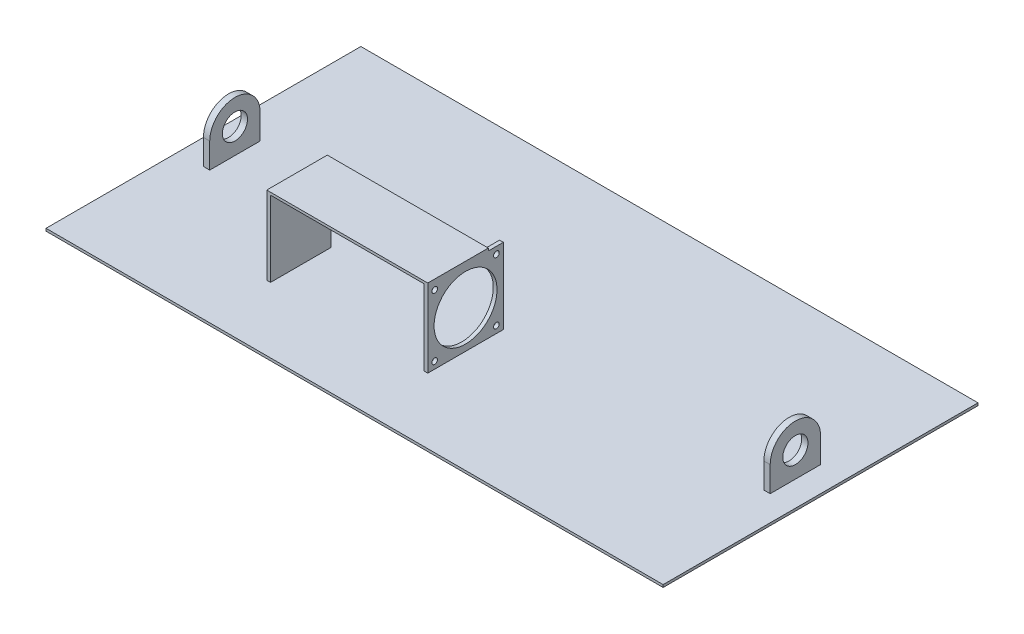
SolidWorks part; units mm, degrees
ref_plane "前视基准面" through (0, 0, 0) normal (0, 0, 1) x (1, 0, 0)
ref_plane "上视基准面" through (0, 0, 0) normal (0, 1, 0) x (1, 0, 0)
ref_plane "右视基准面" through (0, 0, 0) normal (1, 0, 0) x (0, 0, -1)
sketch "草图1" plane through (0, 0, 0) normal (0, 1, 0) x (1, 0, 0)
  line L0 (0, 0) -> (490, 0)
  line L1 (490, 0) -> (490, 250)
  line L2 (490, 250) -> (0, 250)
  line L3 (0, 250) -> (0, 0)
  dimension "D1" = 490
  dimension "D2" = 250
extrude "凸台-拉伸1" add sketch "草图1" along normal blind 2
sketch "草图2" plane through (0, 2, 0) normal (0, 1, 0) x (1, 0, 0)
  line L0 (-50.0701, 125) -> (553.3492, 125) construction
  line L1 (0, 0) -> (490, 0) construction
  line L2 (470, 145) -> (470, 105)
  line L3 (490, 0) -> (490, 250) construction
  line L4 (245, 322.1958) -> (245, -62.0955) construction
  line L5 (465, 145) -> (465, 105)
  line L6 (470, 145) -> (465, 145)
  line L7 (470, 105) -> (465, 105)
  dimension "D1" = 125
  dimension "D2" = 20
  dimension "D3" = 245
  dimension "D4" = 5
  dimension "D5" = 40
extrude "凸台-拉伸2" add sketch "草图2" along normal blind 40
sketch "草图3" plane through (470, 0, 0) normal (1, 0, 0) x (0, 0, -1)
  line L0 (145, 42) -> (145, 2) construction
  line L1 (105, 42) -> (145, 42) construction
  line L2 (125, 42) -> (145, 42)
  line L3 (145, 42) -> (145, 22)
  line L5 (125, 42) -> (105, 42)
  line L6 (105, 42) -> (105, 22)
  arc A0 (145, 22) -> (105, 22) centre (125, 22) ccw
  line M3 (145, 2) -> (145, 42)
  line M4 (145, 42) -> (105, 42)
  line M5 (105, 42) -> (105, 2)
  dimension "D1" = 40
  dimension "D2" = 20
extrude "切除-拉伸1" cut sketch "草图3" against normal blind 40 contours A0 M4 M5 | A0 M3 M4
sketch "草图4" plane through (470, 0, 0) normal (1, 0, 0) x (0, 0, -1)
  arc A1 (145, 22) -> (105, 22) centre (125, 22) ccw construction
  circle A2 centre (125, 22) radius 10
  dimension "D1" = 20
extrude "切除-拉伸2" cut sketch "草图4" against normal blind 40
ref_plane "基准面1" through (245, 0, 0) normal (1, 0, 0) x (0, 0, -1)
mirror "镜向1" about plane through (245, 0, 0) normal (1, 0, 0) of "切除-拉伸1", "凸台-拉伸2", "切除-拉伸2"
sketch "草图5" plane through (0, 2, 0) normal (0, 1, 0) x (1, 0, 0)
  line L0 (-22.3806, 51.93) -> (543.9926, 51.93) construction
  line L1 (0, 0) -> (490, 0) construction
  line L2 (-28.8011, 111.93) -> (523.6073, 111.93) construction
  line L3 (248.19, -63.5388) -> (248.19, 320.9965) construction
  line L4 (245, 322.1958) -> (245, -62.0955) construction
  line L5 (251.19, -63.5388) -> (251.19, 320.9965) construction
  line L6 (248.19, 111.93) -> (251.19, 111.93)
  line L7 (251.19, 111.93) -> (251.19, 51.93)
  line L8 (251.19, 51.93) -> (248.19, 51.93)
  line L9 (248.19, 111.93) -> (248.19, 51.93)
  dimension "D1" = 51.93
  dimension "D2" = 60
  dimension "D3" = 3.19
  dimension "D4" = 3
extrude "凸台-拉伸3" add sketch "草图5" along normal blind 60
sketch "草图6" plane through (248.19, 0, 0) normal (-1, 0, 0) x (0, 0, 1)
  line L0 (-111.93, 2) -> (-51.93, 2) construction
  line L1 (-51.93, 62) -> (-51.93, 2) construction
  line L2 (-111.93, 62) -> (-111.93, 2) construction
  line L3 (-111.93, 62) -> (-51.93, 62) construction
  line L4 (-111.93, 2) -> (-51.93, 2) construction
  line L5 (-51.93, 62) -> (-51.93, 2) construction
  line L6 (-111.93, 62) -> (-111.93, 2) construction
  line L7 (-111.93, 62) -> (-51.93, 62) construction
  line L8 (-111.93, 62) -> (-51.93, 2) construction
  circle A0 centre (-81.93, 32) radius 25
  dimension "D1" = 50
extrude "切除-拉伸3" cut sketch "草图6" against normal up to next
sketch "草图7" plane through (248.19, 0, 0) normal (-1, 0, 0) x (0, 0, 1)
  line L0 (-111.93, 62) -> (-51.93, 62) construction
  line L1 (-51.93, 62) -> (-51.93, 2) construction
  line L2 (-26.344, 32) -> (-132.1591, 32) construction
  line L3 (-111.93, 2) -> (-51.93, 2) construction
  line L4 (-81.93, 76.2726) -> (-81.93, -5.4085) construction
  circle A0 centre (-57.43, 56.5) radius 5.5 construction
  circle A1 centre (-57.43, 56.5) radius 2.25
  circle A4 centre (-57.43, 7.5) radius 2.25
  circle A5 centre (-106.43, 7.5) radius 2.25
  circle A6 centre (-106.43, 56.5) radius 2.25
  dimension "D1" = 11
  dimension "D2" = 4.5
  dimension "D3" = 30
  dimension "D4" = 30
extrude "切除-拉伸4" cut sketch "草图7" against normal up to next
sketch "草图9" plane through (0, 2, 0) normal (0, 1, 0) x (1, 0, 0)
  line L0 (123.35, 321.6764) -> (123.35, -57.2319) construction
  line L1 (0, 250) -> (0, 0) construction
  line L2 (126.35, 321.6764) -> (126.35, -57.2319) construction
  line L3 (-52.4211, 100) -> (503.8762, 100) construction
  line L4 (0, 0) -> (490, 0) construction
  line L5 (-12.8323, 51.93) -> (306.574, 51.93) construction
  line L6 (123.35, 100) -> (126.35, 100)
  line L7 (126.35, 100) -> (126.35, 51.93)
  line L8 (126.35, 51.93) -> (123.35, 51.93)
  line L9 (123.35, 51.93) -> (123.35, 100)
  dimension "D1" = 123.35
  dimension "D2" = 3
  dimension "D3" = 100
extrude "凸台-拉伸4" add sketch "草图9" along normal blind 60
sketch "草图10" plane through (0, 62, 0) normal (0, 1, 0) x (1, 0, 0)
  line L0 (123.35, 100) -> (251.19, 100)
  line L1 (251.19, 51.93) -> (251.19, 111.93) construction
  line L2 (251.19, 100) -> (251.19, 51.93)
  line L3 (251.19, 51.93) -> (123.35, 51.93)
  line L4 (123.35, 51.93) -> (123.35, 100)
extrude "凸台-拉伸5" add sketch "草图10" along normal blind 2
